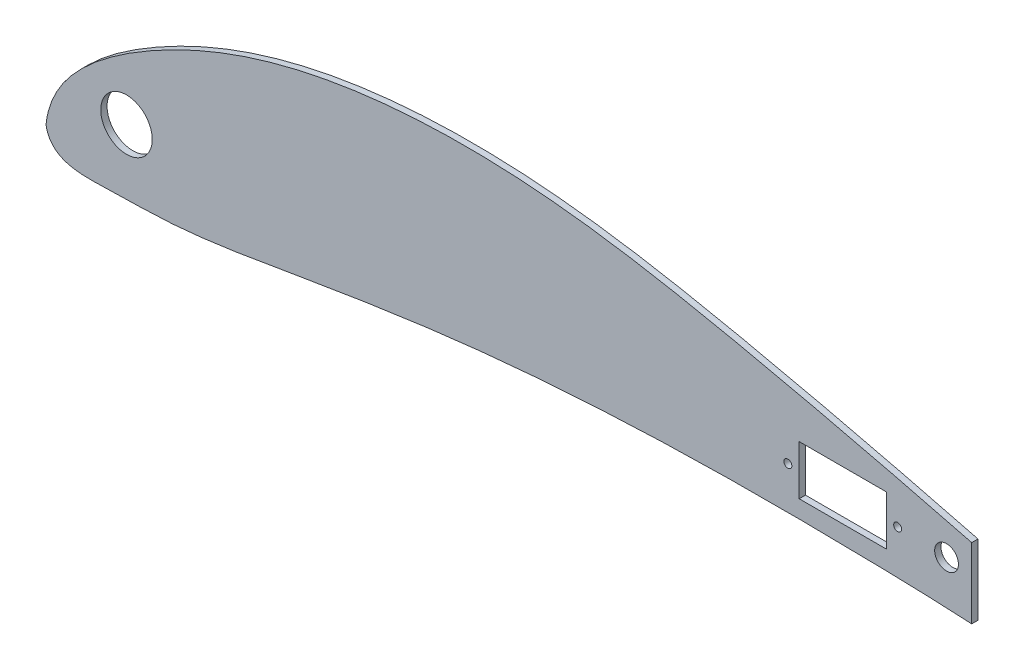
SolidWorks part; units mm, degrees
material "Balsa"
ref_plane "Front Plane" through (0, 0, 0) normal (0, 0, 1) x (1, 0, 0)
ref_plane "Top Plane" through (0, 0, 0) normal (0, 1, 0) x (1, 0, 0)
ref_plane "Right Plane" through (0, 0, 0) normal (1, 0, 0) x (0, 0, -1)
sketch "Sketch1" plane through (0, 0, 0) normal (0, 0, 1) x (1, 0, 0)
  spline S0 degree 3 poles (0.0006, 0.0001) (0.8106, 7.3592) (8.6491, 17.8566) (26.2867, 29.9752) (52.1111, 42.0692) (89.5976, 49.2908) (131.4008, 47.8848) (173.2567, 40.0411) (217.9611, 29.613) (256.9521, 19.5289) (290.3598, 8.711) (301.2732, 4.3828) (314.8169, -0.5162) (309.8463, 0.0001) knots 0 0 0 0 0.060864 0.113688 0.188609 0.312909 0.448482 0.557612 0.691544 0.852438 0.929756 0.976058 1 1 1 1
  spline S1 degree 3 poles (309.8463, 0.0001) (303.9568, 1.471) (293.9895, 2.094) (276.264, 4.5144) (260.8463, 5.4274) (235.8588, 7.8703) (205.1014, 8.8381) (157.7186, 9.0307) (110.4973, 6.1815) (66.5062, -0.5867) (36.4547, -6.0985) (15.3166, -6.1891) (1.2307, -6.9241) (0.0006, 0.0001) knots 0 0 0 0 0.057787 0.095275 0.171021 0.205339 0.335319 0.464904 0.658702 0.785512 0.893517 0.943092 1 1 1 1
extrude "Boss-Extrude1" add sketch "Sketch1" along normal blind 1.5875
sketch "Sketch2" plane through (0, 0, 1.5875) normal (0, 0, 1) x (1, 0, 0)
  circle A0 centre (20.32, 10.16) radius 6.5
  circle A1 centre (227.2963, 19.0501) radius 3
  dimension "D2" = 13
  dimension "D3" = 6
  dimension "D6" = 20.32
  dimension "D1" = 82.55
  dimension "D4" = 19.05
  dimension "D5" = 10.16
extrude "Cut-Extrude1" cut sketch "Sketch2" against normal through all
sketch "Sketch3" plane through (0, 0, 1.5875) normal (0, 0, 1) x (1, 0, 0)
  line L1 (350.4863, -6.3499) -> (233.6463, -6.3499)
  line L2 (350.4863, -6.3499) -> (350.4863, 44.4501)
  line L3 (350.4863, 44.4501) -> (233.6463, 44.4501)
  line L4 (233.6463, -6.3499) -> (233.6463, 44.4501)
  circle A0 centre (227.2963, 19.0501) radius 3 construction
  dimension "D1" = 6.35
  dimension "D2" = 116.84
  dimension "D3" = 50.8
  dimension "D4" = 44.45
extrude "Cut-Extrude2" cut sketch "Sketch3" against normal through all contours L3 L4 L1 L2
sketch "Sketch4" plane through (0, 0, 1.5875) normal (0, 0, 1) x (1, 0, 0)
  line L0 (190.0992, 19.5181) -> (187.2492, 19.5181) construction
  line L1 (190.0992, 25.7681) -> (212.0992, 25.7681)
  line L2 (190.0992, 25.7681) -> (190.0992, 13.2681)
  line L3 (190.0992, 13.2681) -> (212.0992, 13.2681)
  line L4 (212.0992, 25.7681) -> (212.0992, 13.2681)
  line L5 (212.0992, 19.5181) -> (214.9492, 19.5181) construction
  circle A0 centre (214.9492, 19.5181) radius 1.0008
  circle A1 centre (187.2492, 19.5181) radius 1.0008
  dimension "D4" = 2.0015
  dimension "D1" = 2.85
  dimension "D2" = 22
  dimension "D3" = 12.5
extrude "Cut-Extrude3" cut sketch "Sketch4" against normal through all
